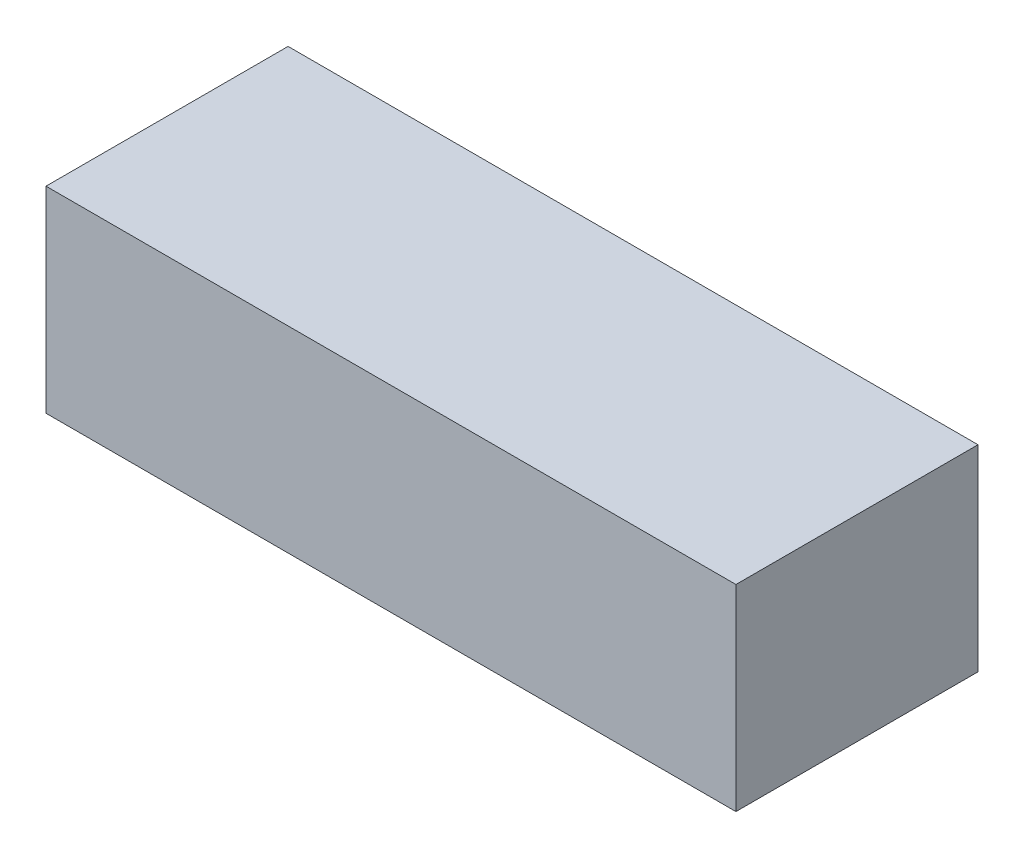
SolidWorks part; units mm, degrees
ref_plane "Front Plane" through (0, 0, 0) normal (0, 0, 1) x (1, 0, 0)
ref_plane "Top Plane" through (0, 0, 0) normal (0, 1, 0) x (1, 0, 0)
ref_plane "Right Plane" through (0, 0, 0) normal (1, 0, 0) x (0, 0, -1)
sketch "Sketch1" plane through (0, 0, 0) normal (0, 1, 0) x (1, 0, 0)
  line L1 (0, 0) -> (228, 0)
  line L2 (0, 0) -> (0, 80)
  line L3 (0, 80) -> (228, 80)
  line L4 (228, 0) -> (228, 80)
  dimension "D1" = 228
  dimension "D2" = 80
extrude "Boss-Extrude1" add sketch "Sketch1" along normal blind 65
